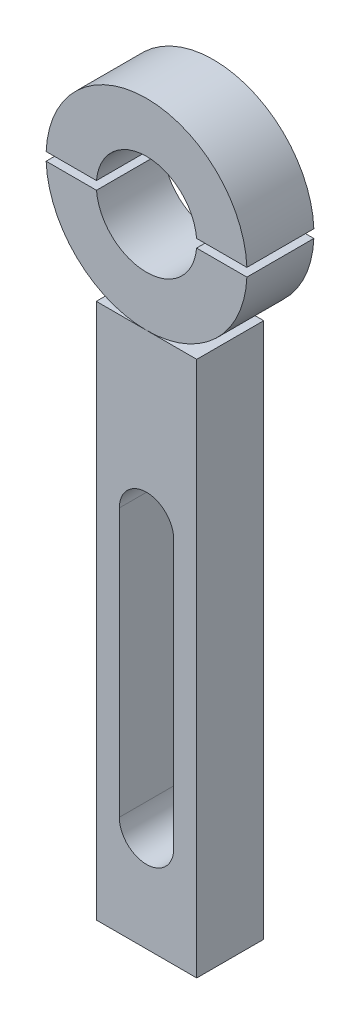
SolidWorks part; units mm, degrees
ref_plane "Front" through (0, 0, 0) normal (0, 0, 1) x (1, 0, 0)
ref_plane "Top" through (0, 0, 0) normal (0, 1, 0) x (1, 0, 0)
ref_plane "Right" through (0, 0, 0) normal (1, 0, 0) x (0, 0, -1)
sketch "Sketch1" plane through (0, 0, 0) normal (0, 0, 1) x (1, 0, 0)
  line L0 (-19.0335, 0.7938) -> (-9.4919, 0.7938)
  line L1 (19.0335, -0.7937) -> (9.4919, -0.7937)
  line L2 (9.4919, 0.7938) -> (19.0335, 0.7938)
  line L3 (-9.4919, -0.7937) -> (-19.0335, -0.7937)
  arc A0 (9.4919, 0.7938) -> (-9.4919, 0.7938) centre (0, 0) ccw
  arc A1 (19.0335, 0.7938) -> (-19.0335, 0.7938) centre (0, 0) ccw
  arc A2 (-9.4919, -0.7937) -> (9.4919, -0.7937) centre (0, 0) ccw
  arc A3 (-19.0335, -0.7937) -> (19.0335, -0.7937) centre (0, 0) ccw
  dimension "D1" = 38.1
  dimension "D2" = 19.05
  dimension "D3" = 1.5875
extrude "Extrude1" add sketch "Sketch1" along normal mid plane 12.7
sketch "Sketch2" plane through (0, 0, 6.35) normal (0, 0, 1) x (1, 0, 0)
  line L1 (-9.525, -19.05) -> (9.525, -19.05)
  line L2 (-9.525, -19.05) -> (-9.525, -120.65)
  line L3 (-9.525, -120.65) -> (9.525, -120.65)
  line L4 (9.525, -19.05) -> (9.525, -120.65)
  arc A0 (-19.0335, -0.7937) -> (19.0335, -0.7937) centre (0, 0) ccw construction
  point P4 (0, -19.05)
  dimension "D1" = 19.05
  dimension "D2" = 101.6
extrude "Extrude2" add sketch "Sketch2" against normal blind 12.7
sketch "Sketch3" plane through (0, 0, 6.35) normal (0, 0, 1) x (1, 0, 0)
  line L0 (-5.1594, -101.6) -> (-5.1594, -50.8)
  line L1 (5.1594, -50.8) -> (5.1594, -101.6)
  arc A0 (-5.1594, -101.6) -> (5.1594, -101.6) centre (0, -101.6) ccw
  arc A1 (-9.4919, -0.7937) -> (9.4919, -0.7937) centre (0, 0) ccw construction
  arc A2 (-5.1594, -50.8) -> (5.1594, -50.8) centre (0, -50.8) cw
  dimension "D1" = 101.6
  dimension "D2" = 10.3187
  dimension "D3" = 50.8
extrude "Cut-Extrude1" cut sketch "Sketch3" against normal through all
